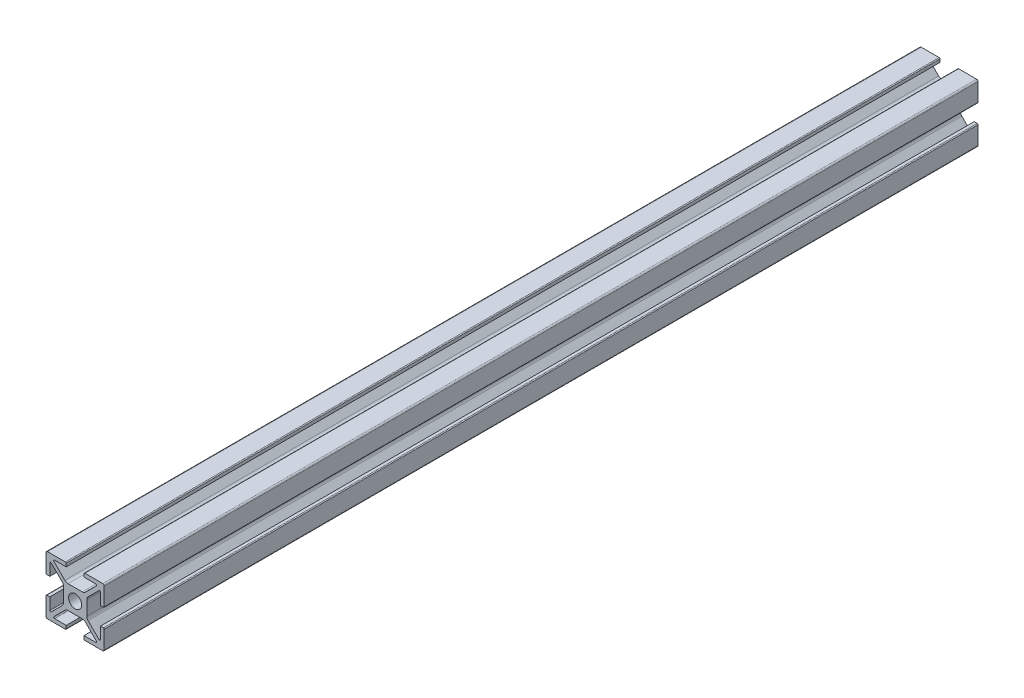
SolidWorks part; units mm, degrees
material "6063-T5"
material "6063-T5"
ref_plane "Front" through (0, 0, 0) normal (0, 0, 1) x (1, 0, 0)
ref_plane "Top" through (0, 0, 0) normal (0, 1, 0) x (1, 0, 0)
ref_plane "Right" through (0, 0, 0) normal (1, 0, 0) x (0, 0, -1)
sketch "Esboço1" plane through (0, 0, 0) normal (1, 0, 0) x (0, 0, -1)
  line L0 (0, 0) -> (-300, 0)
  dimension "D1" = 300
other "Quadrado PF20-21 - PERFIL 2020 T-SLOT 6MM(1)"
ref_plane "Plano1" through (0, 0, 0) normal (0, 0, 1) x (0, -1, 0)
sketch "Esboço11" plane through (0, 0, 0) normal (0, 0, 1) x (0, -1, 0)
  line L0 (8.1879, -7.2686) -> (4.4393, -3.5201)
  line L1 (4, -2.4594) -> (4, 2.4594)
  line L2 (4.4393, 3.5201) -> (8.1879, 7.2686)
  line L3 (8.7, 7.0565) -> (8.7, 3.05)
  line L4 (10, 3.35) -> (10, 9.5)
  line L5 (9.5, 10) -> (3.35, 10)
  line L6 (3.05, 8.7) -> (7.0565, 8.7)
  line L7 (7.2686, 8.1879) -> (3.5201, 4.4393)
  line L8 (2.4594, 4) -> (-2.4594, 4)
  line L9 (-3.5201, 4.4393) -> (-7.2686, 8.1879)
  line L10 (-7.0565, 8.7) -> (-3.05, 8.7)
  line L11 (-3.35, 10) -> (-9.5, 10)
  line L12 (-10, 9.5) -> (-10, 3.35)
  line L13 (-8.7, 3.05) -> (-8.7, 7.0565)
  line L14 (-8.1879, 7.2686) -> (-4.4393, 3.5201)
  line L15 (-4, 2.4594) -> (-4, -2.4594)
  line L16 (-4.4393, -3.5201) -> (-8.1879, -7.2686)
  line L17 (-8.7, -7.0565) -> (-8.7, -3.05)
  line L18 (-10, -3.35) -> (-10, -9.5)
  line L19 (-9.5, -10) -> (-3.35, -10)
  line L20 (-3.05, -8.7) -> (-7.0565, -8.7)
  line L21 (-7.2686, -8.1879) -> (-3.5201, -4.4393)
  line L22 (-2.4594, -4) -> (2.4594, -4)
  line L23 (3.5201, -4.4393) -> (7.2686, -8.1879)
  line L24 (7.0565, -8.7) -> (3.05, -8.7)
  line L25 (3.05, -8.7) -> (3.05, -9.7)
  line L26 (3.35, -10) -> (9.5, -10)
  line L27 (10, -9.5) -> (10, -3.35)
  line L28 (8.7, -3.05) -> (9.7, -3.05)
  line L29 (8.7, -3.05) -> (8.7, -7.0565)
  line L30 (-3.05, 9.7) -> (-3.05, 8.7)
  line L31 (-9.7, -3.05) -> (-8.7, -3.05)
  line L32 (3.05, 9.7) -> (3.05, 8.7)
  line L33 (-9.7, 3.05) -> (-8.7, 3.05)
  line L34 (-3.05, -8.7) -> (-3.05, -9.7)
  line L35 (8.7, 3.05) -> (9.7, 3.05)
  circle A0 centre (0, 0) radius 2.25
  arc A1 (8.1879, -7.2686) -> (8.7, -7.0565) centre (8.4, -7.0565) ccw
  arc A2 (4, -2.4594) -> (4.4393, -3.5201) centre (5.5, -2.4594) ccw
  arc A3 (4.4393, 3.5201) -> (4, 2.4594) centre (5.5, 2.4594) ccw
  arc A4 (8.7, 7.0565) -> (8.1879, 7.2686) centre (8.4, 7.0565) ccw
  arc A5 (10, 9.5) -> (9.5, 10) centre (9.5, 9.5) ccw
  arc A6 (7.2686, 8.1879) -> (7.0565, 8.7) centre (7.0565, 8.4) ccw
  arc A7 (2.4594, 4) -> (3.5201, 4.4393) centre (2.4594, 5.5) ccw
  arc A8 (-3.5201, 4.4393) -> (-2.4594, 4) centre (-2.4594, 5.5) ccw
  arc A9 (-7.0565, 8.7) -> (-7.2686, 8.1879) centre (-7.0565, 8.4) ccw
  arc A10 (-9.5, 10) -> (-10, 9.5) centre (-9.5, 9.5) ccw
  arc A11 (-8.1879, 7.2686) -> (-8.7, 7.0565) centre (-8.4, 7.0565) ccw
  arc A12 (-4, 2.4594) -> (-4.4393, 3.5201) centre (-5.5, 2.4594) ccw
  arc A13 (-4.4393, -3.5201) -> (-4, -2.4594) centre (-5.5, -2.4594) ccw
  arc A14 (-8.7, -7.0565) -> (-8.1879, -7.2686) centre (-8.4, -7.0565) ccw
  arc A15 (-10, -9.5) -> (-9.5, -10) centre (-9.5, -9.5) ccw
  arc A16 (-7.2686, -8.1879) -> (-7.0565, -8.7) centre (-7.0565, -8.4) ccw
  arc A17 (-2.4594, -4) -> (-3.5201, -4.4393) centre (-2.4594, -5.5) ccw
  arc A18 (3.5201, -4.4393) -> (2.4594, -4) centre (2.4594, -5.5) ccw
  arc A19 (7.0565, -8.7) -> (7.2686, -8.1879) centre (7.0565, -8.4) ccw
  arc A20 (9.5, -10) -> (10, -9.5) centre (9.5, -9.5) ccw
  arc A21 (-9.7, 3.05) -> (-10, 3.35) centre (-9.7, 3.35) cw
  arc A22 (-9.7, -3.05) -> (-10, -3.35) centre (-9.7, -3.35) ccw
  arc A23 (-3.05, -9.7) -> (-3.35, -10) centre (-3.35, -9.7) cw
  arc A24 (3.05, -9.7) -> (3.35, -10) centre (3.35, -9.7) ccw
  arc A25 (9.7, -3.05) -> (10, -3.35) centre (9.7, -3.35) cw
  arc A26 (9.7, 3.05) -> (10, 3.35) centre (9.7, 3.35) ccw
  arc A27 (3.05, 9.7) -> (3.35, 10) centre (3.35, 9.7) cw
  arc A28 (-3.05, 9.7) -> (-3.35, 10) centre (-3.35, 9.7) ccw
  point P0 (0, 10)
  point P1 (-10, 10)
  point P2 (0, 0)
  point P3 (10, 10)
  point P4 (10, 0)
  point P5 (10, -10)
  point P6 (0, -10)
  point P7 (-10, -10)
  point P8 (-10, 0)
  point P9 (0, 0)
  point P88 (0, 0)
